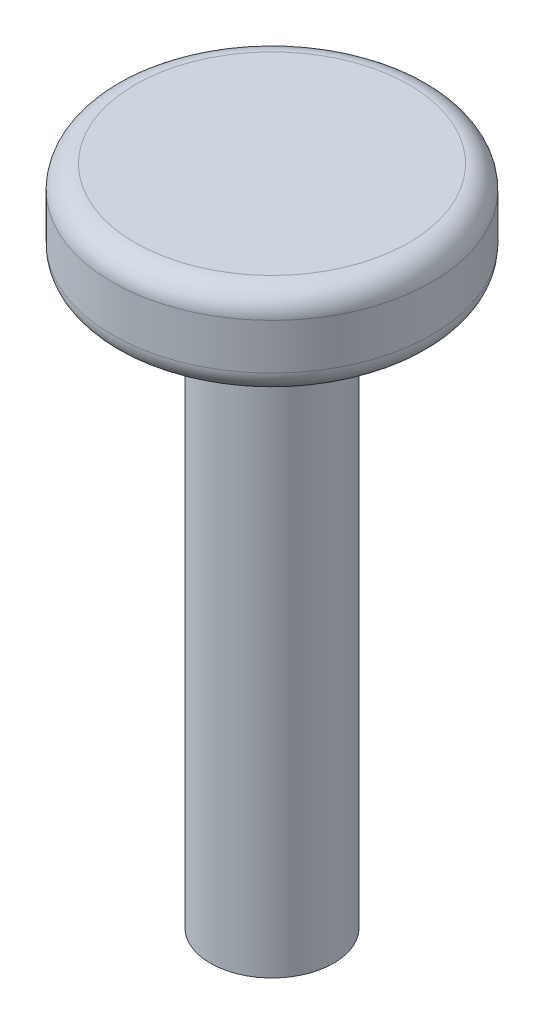
SolidWorks part; units mm, degrees
ref_plane "Front Plane" through (0, 0, 0) normal (0, 0, 1) x (1, 0, 0)
ref_plane "Top Plane" through (0, 0, 0) normal (0, 1, 0) x (1, 0, 0)
ref_plane "Right Plane" through (0, 0, 0) normal (1, 0, 0) x (0, 0, -1)
sketch "Sketch1" plane through (0, 0, 0) normal (0, 1, 0) x (1, 0, 0)
  circle A0 centre (0, 0) radius 1.35
  dimension "D1" = 2.7
extrude "Boss-Extrude1" add sketch "Sketch1" along normal blind 12.5
sketch "Sketch2" plane through (0, 12.5, 0) normal (0, 1, 0) x (1, 0, 0)
  circle A0 centre (0, 0) radius 3.5
  dimension "D1" = 7
extrude "Boss-Extrude2" add sketch "Sketch2" along normal blind 2
fillet "Fillet1" radius 0.5 2 edges at (0, 12.5, 3.5) (0, 14.5, 3.5)
